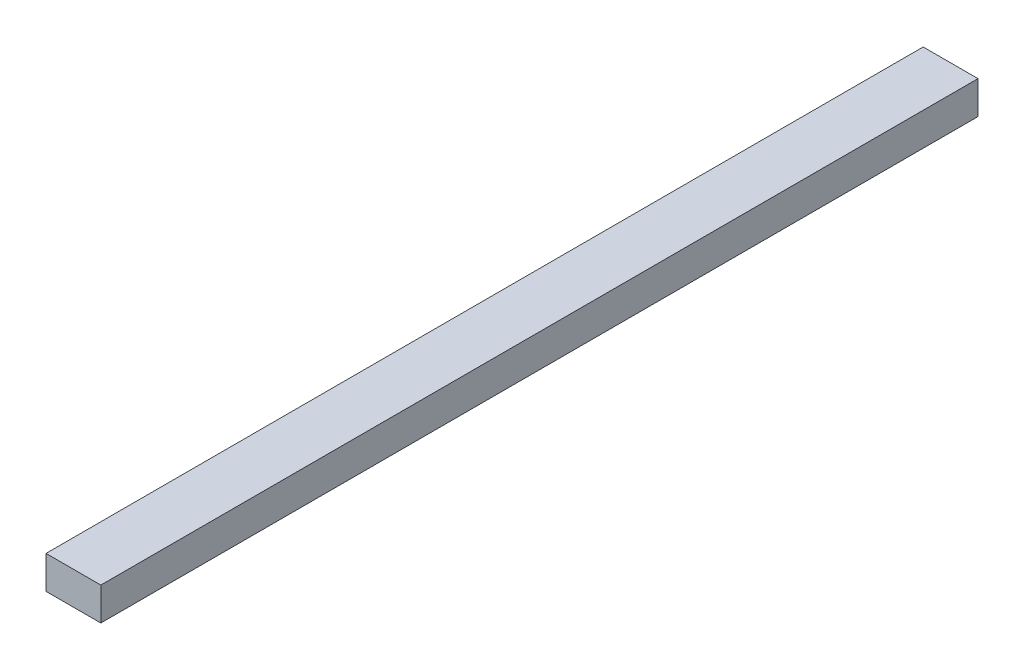
SolidWorks part; units mm, degrees
material "Красное дерево"
ref_plane "Спереди" through (0, 0, 0) normal (0, 0, 1) x (1, 0, 0)
ref_plane "Сверху" through (0, 0, 0) normal (0, 1, 0) x (1, 0, 0)
ref_plane "Справа" through (0, 0, 0) normal (1, 0, 0) x (0, 0, -1)
sketch "Эскиз1" plane through (0, 0, 0) normal (0, 0, 1) x (1, 0, 0)
  line L1 (-25, -15) -> (25, -15)
  line L2 (-25, -15) -> (-25, 15)
  line L3 (-25, 15) -> (25, 15)
  line L4 (25, -15) -> (25, 15)
  line L5 (0, 15) -> (0, -15) construction
  line L6 (-25, 0) -> (25, 0) construction
  point P0 (0, 0)
  dimension "D1" = 50
  dimension "D2" = 30
extrude "Бобышка-Вытянуть1" add sketch "Эскиз1" along normal mid plane 800
